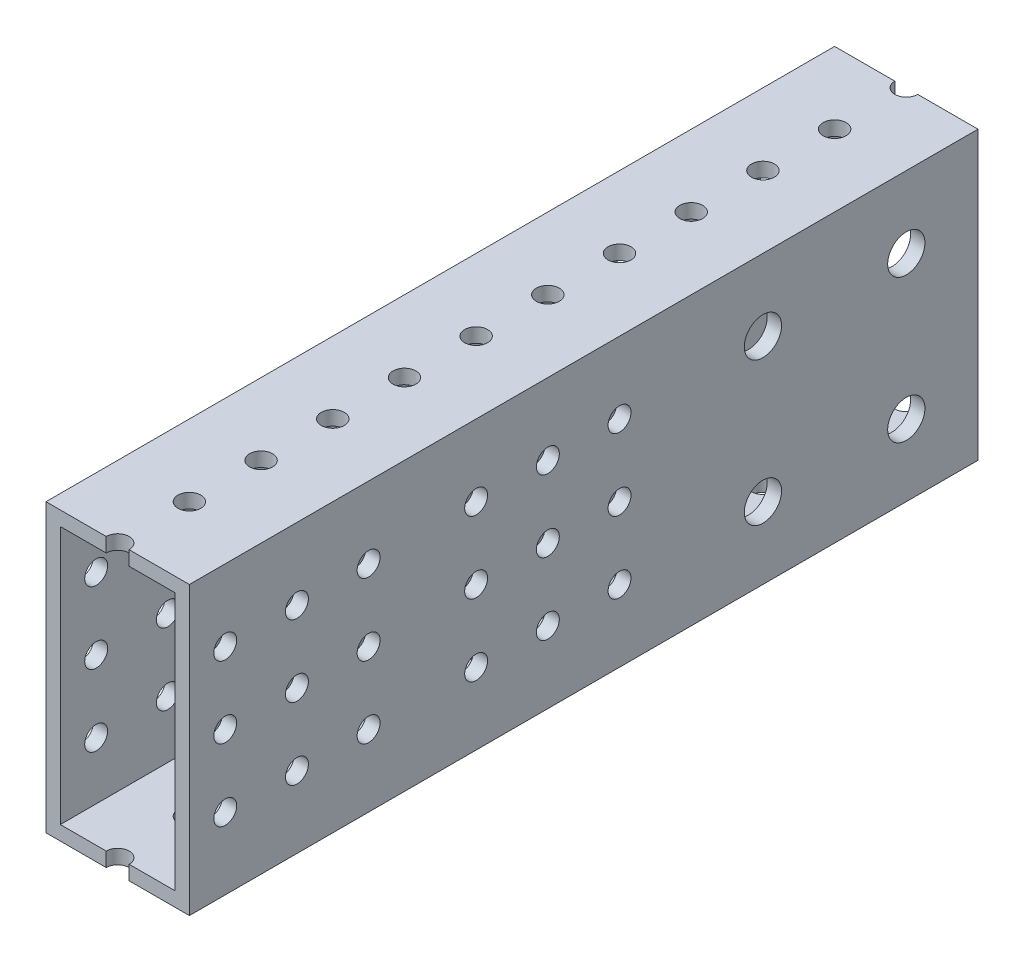
SolidWorks part; units mm, degrees
ref_plane "Front Plane" through (0, 0, 0) normal (0, 0, 1) x (1, 0, 0)
ref_plane "Top Plane" through (0, 0, 0) normal (0, 1, 0) x (1, 0, 0)
ref_plane "Right Plane" through (0, 0, 0) normal (1, 0, 0) x (0, 0, -1)
sketch "Sketch1" plane through (0, 0, 0) normal (0, 0, 1) x (1, 0, 0)
  line L0 (-10.16, 22.86) -> (10.16, 22.86)
  line L1 (-12.7, -25.4) -> (12.7, -25.4)
  line L2 (-12.7, -25.4) -> (-12.7, 25.4)
  line L3 (-12.7, 25.4) -> (12.7, 25.4)
  line L4 (12.7, -25.4) -> (12.7, 25.4)
  line L5 (-12.7, -25.4) -> (12.7, 25.4) construction
  line L6 (-12.7, 25.4) -> (12.7, -25.4) construction
  line L7 (10.16, -22.86) -> (10.16, 22.86)
  line L8 (-10.16, -22.86) -> (10.16, -22.86)
  line L9 (-10.16, -22.86) -> (-10.16, 22.86)
  point P0 (0, 0)
  dimension "D1" = 25.4
  dimension "D2" = 50.8
  dimension "D3" = 2.54
extrude "Boss-Extrude1" add sketch "Sketch1" along normal blind 114.3
sketch "Sketch6" plane through (0, 0, 114.3) normal (0, 0, 1) x (1, 0, 0)
  line L1 (-10.16, 22.86) -> (-10.16, -22.86)
  line L2 (-10.16, -22.86) -> (10.16, -22.86)
  line L3 (10.16, -22.86) -> (10.16, 22.86)
  line L4 (12.7, -25.4) -> (12.7, 25.4)
  line L5 (12.7, 25.4) -> (-12.7, 25.4)
  line L6 (-12.7, 25.4) -> (-12.7, -25.4)
  line L7 (-12.7, -25.4) -> (12.7, -25.4)
  line L8 (12.7, -25.4) -> (12.7, 25.4)
  line L9 (12.7, 25.4) -> (-12.7, 25.4)
  line L10 (-12.7, 25.4) -> (-12.7, -25.4)
  line L11 (-12.7, -25.4) -> (12.7, -25.4)
  line L12 (10.16, 22.86) -> (-10.16, 22.86)
  dimension "D1" = 0
  dimension "D2" = 2.54
extrude "Boss-Extrude4" add sketch "Sketch6" along normal blind 38.1
sketch "Sketch2" plane through (0, 25.4, 0) normal (0, 1, 0) x (1, 0, 0)
  line L0 (12.7, 0) -> (-12.7, 0) construction
  circle A0 centre (0, 0) radius 2.032
  circle A1 centre (0, -12.7) radius 2.032
  circle A2 centre (0, -25.4) radius 2.032
  circle A3 centre (0, -38.1) radius 2.032
  circle A4 centre (0, -50.8) radius 2.032
  circle A5 centre (0, -63.5) radius 2.032
  circle A6 centre (0, -76.2) radius 2.032
  circle A7 centre (0, -88.9) radius 2.032
  circle A8 centre (0, -101.6) radius 2.032
  circle A9 centre (0, -114.3) radius 2.032
  circle A10 centre (0, -127) radius 2.032
  circle A11 centre (0, -139.7) radius 2.032
  circle A12 centre (0, -152.4) radius 2.032
  circle A13 centre (0, -165.1) radius 2.032
  circle A14 centre (0, -177.8) radius 2.032
  circle A15 centre (0, -190.5) radius 2.032
  circle A16 centre (0, -203.2) radius 2.032
  circle A17 centre (0, -215.9) radius 2.032
  circle A18 centre (0, -228.6) radius 2.032
  circle A19 centre (0, -241.3) radius 2.032
  dimension "D1" = 4.064
  dimension "D2" = 20
extrude "Cut-Extrude1" cut sketch "Sketch2" against normal through all
sketch "Sketch3" plane through (-12.7, 0, 0) normal (-1, 0, 0) x (0, 0, 1)
  line L0 (152.4, 25.4) -> (0, 25.4) construction
  line L11 (101.6, 0) -> (107.95, 0) construction
  line L12 (107.95, 0) -> (107.95, -35.1614) construction
  circle A0 centre (101.6, 12.7) radius 2.032
  circle A1 centre (101.6, 0) radius 2.032
  circle A2 centre (101.6, -12.7) radius 2.032
  circle A3 centre (88.9, 0) radius 2.032
  circle A4 centre (88.9, -12.7) radius 2.032
  circle A5 centre (76.2, 0) radius 2.032
  circle A6 centre (76.2, -12.7) radius 2.032
  circle A7 centre (88.9, 12.7) radius 2.032
  circle A8 centre (76.2, 12.7) radius 2.032
  dimension "D2" = 12.7
  dimension "D1" = 4.064
  dimension "D3" = 6.35
  dimension "D6" = 107.95
  dimension "D4" = 3
  dimension "D5" = 3
extrude "Cut-Extrude2" cut sketch "Sketch3" against normal through all and the other way through all
sketch "Sketch7" plane through (0, 0, 0) normal (0, 0, -1) x (-1, 0, 0)
  line L1 (-12.7, -25.4) -> (12.7, -25.4)
  line L2 (-12.7, -25.4) -> (-12.7, 25.4)
  line L3 (-12.7, 25.4) -> (12.7, 25.4)
  line L4 (12.7, -25.4) -> (12.7, 25.4)
extrude "Cut-Extrude3" cut sketch "Sketch7" against normal blind 12.7
sketch "Sketch8" plane through (-12.7, 0, 0) normal (-1, 0, 0) x (0, 0, 1)
  line L0 (152.4, -25.4) -> (12.7, -25.4) construction
  line L1 (12.7, 25.4) -> (63.5, 25.4) construction
  line L2 (12.7, 25.4) -> (12.7, -25.4) construction
  line L3 (12.7, -25.4) -> (63.5, -25.4) construction
  line L4 (63.5, 25.4) -> (63.5, -25.4) construction
  line L5 (63.5, 0) -> (12.7, 0) construction
  line L6 (38.1, 25.4) -> (38.1, -25.4) construction
  circle A0 centre (25.4, 12.7) radius 3.302
  circle A1 centre (25.4, -12.7) radius 3.302
  circle A2 centre (50.8, -12.7) radius 3.302
  circle A3 centre (50.8, 12.7) radius 3.302
  dimension "D2" = 6.604
  dimension "D1" = 50.8
  dimension "D3" = 12.7
  dimension "D4" = 12.7
extrude "Cut-Extrude5" cut sketch "Sketch8" against normal through all
sketch "Sketch9" plane through (-12.7, 0, 0) normal (-1, 0, 0) x (0, 0, 1)
  line L0 (152.4, 25.4) -> (152.4, -25.4) construction
  line L1 (152.4, 25.4) -> (12.7, 25.4) construction
  circle A0 centre (146.05, 12.7) radius 2.032
  circle A1 centre (146.05, 0) radius 2.032
  circle A2 centre (146.05, -12.7) radius 2.032
  circle A3 centre (133.35, 0) radius 2.032
  circle A4 centre (133.35, -12.7) radius 2.032
  circle A5 centre (120.65, 0) radius 2.032
  circle A6 centre (120.65, -12.7) radius 2.032
  circle A7 centre (133.35, 12.7) radius 2.032
  circle A8 centre (120.65, 12.7) radius 2.032
  dimension "D1" = 4.064
  dimension "D2" = 6.35
  dimension "D3" = 12.7
  dimension "D4" = 3
  dimension "D5" = 3
extrude "Cut-Extrude6" cut sketch "Sketch9" against normal through all
